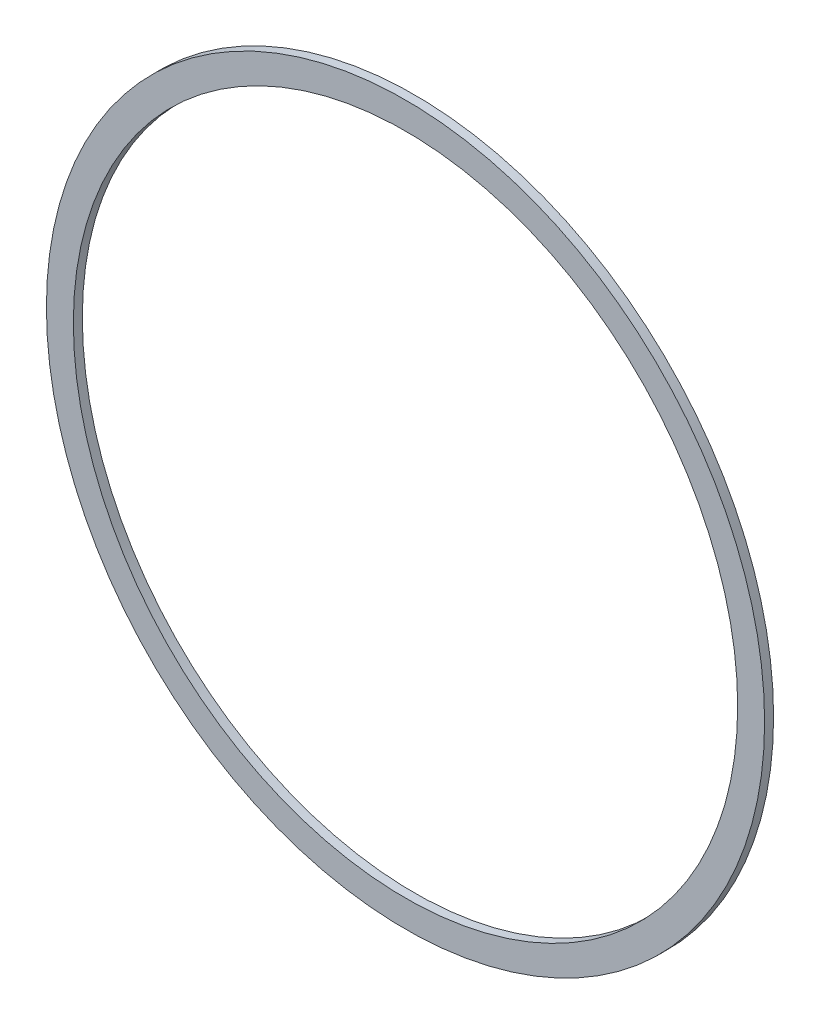
SolidWorks part; units mm, degrees
ref_plane "Front Plane" through (0, 0, 0) normal (0, 0, 1) x (1, 0, 0)
ref_plane "Top Plane" through (0, 0, 0) normal (0, 1, 0) x (1, 0, 0)
ref_plane "Right Plane" through (0, 0, 0) normal (1, 0, 0) x (0, 0, -1)
sketch "Sketch1" plane through (0, 0, 0) normal (0, 0, 1) x (1, 0, 0)
  circle A0 centre (0, 0) radius 37
  circle A1 centre (0, 0) radius 40
  dimension "D1" = 80
  dimension "D2" = 74
extrude "Boss-Extrude1" add sketch "Sketch1" along normal blind 1
